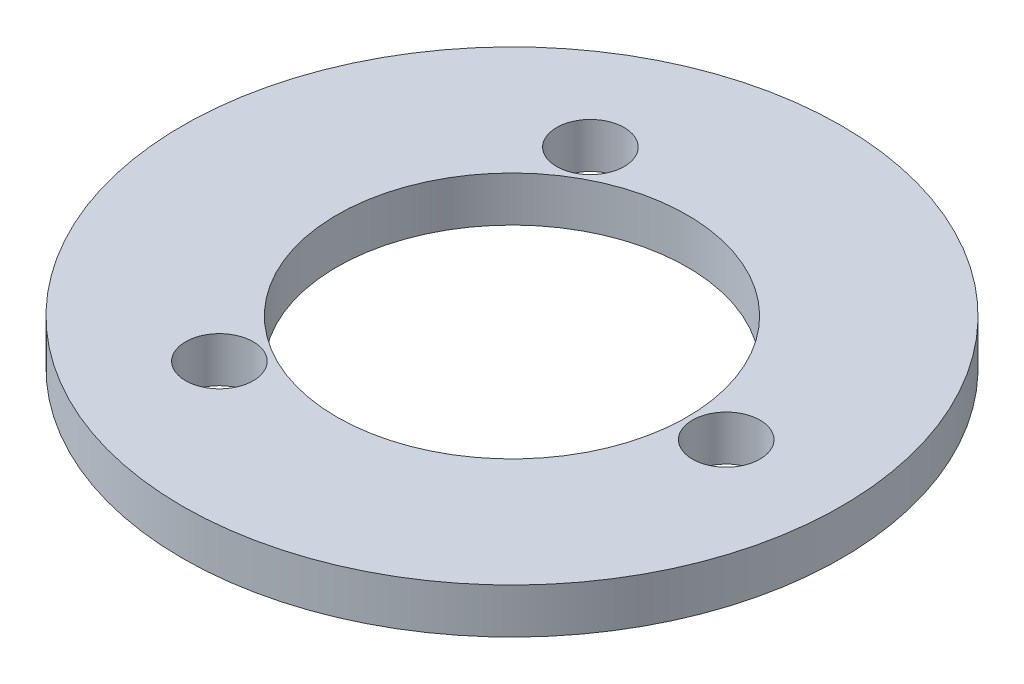
SolidWorks part; units mm, degrees
ref_plane "前视基准面" through (0, 0, 0) normal (0, 0, 1) x (1, 0, 0)
ref_plane "上视基准面" through (0, 0, 0) normal (0, 1, 0) x (1, 0, 0)
ref_plane "右视基准面" through (0, 0, 0) normal (1, 0, 0) x (0, 0, -1)
sketch "Sketch1" plane through (0, 0, 0) normal (0, 1, 0) x (1, 0, 0)
  line L5 (-58.1347, 25.3602) -> (-14.6601, 9.5206) construction
  line L6 (-58.1347, 9.5206) -> (-14.6601, 25.3602) construction
  circle A0 centre (-32.2459, 16.786) radius 14.6166
  circle A1 centre (-32.2459, 16.786) radius 7.7667
  circle A2 centre (-36.9959, 8.5588) radius 1.5 construction
  circle A3 centre (-36.9959, 25.0133) radius 1.5 construction
  circle A4 centre (-22.7459, 16.7861) radius 1.5 construction
  circle A5 centre (-36.9959, 8.5588) radius 1.5
  circle A6 centre (-36.9959, 25.0133) radius 1.5
  circle A7 centre (-22.7459, 16.7861) radius 1.5
  point P0 (-36.3974, 17.4404)
extrude "Boss-Extrude1" add sketch "Sketch1" along normal blind 2
